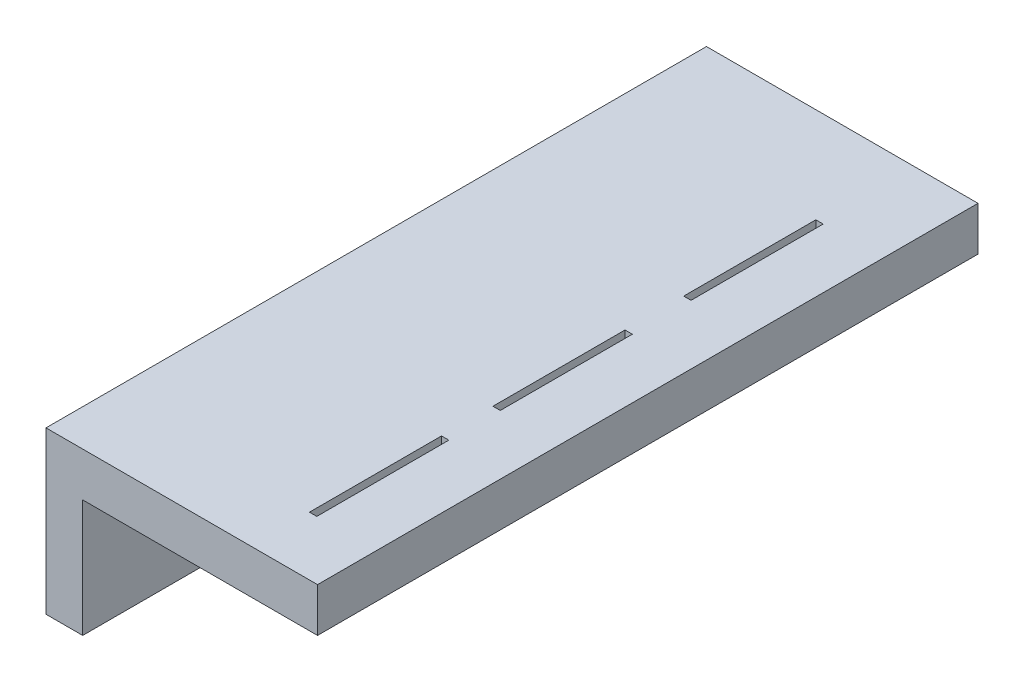
SolidWorks part; units mm, degrees
ref_plane "前视基准面" through (0, 0, 0) normal (0, 0, 1) x (1, 0, 0)
ref_plane "上视基准面" through (0, 0, 0) normal (0, 1, 0) x (1, 0, 0)
ref_plane "右视基准面" through (0, 0, 0) normal (1, 0, 0) x (0, 0, -1)
sketch "Sketch1" plane through (0, 0, 0) normal (0, 1, 0) x (1, 0, 0)
  line L1 (0, 0) -> (70.4, 0)
  line L2 (0, 0) -> (0, 2)
  line L3 (0, 2) -> (70.4, 2)
  line L4 (70.4, 0) -> (70.4, 2)
  dimension "D1" = 70.4
  dimension "D2" = 2
extrude "Boss-Extrude2" add sketch "Sketch1" along normal blind 10
sketch "Sketch2" plane through (0, 10, 0) normal (0, 1, 0) x (1, 0, 0)
  line L1 (0, 2) -> (2, 2)
  line L2 (0, 2) -> (0, 57)
  line L3 (0, 57) -> (2, 57)
  line L4 (2, 2) -> (2, 57)
  line L5 (70.4, 2) -> (68.4, 2)
  line L6 (70.4, 2) -> (70.4, 57)
  line L7 (70.4, 57) -> (68.4, 57)
  line L8 (68.4, 2) -> (68.4, 57)
  dimension "D1" = 55
  dimension "D2" = 2
  dimension "D3" = 2
extrude "Boss-Extrude3" add sketch "Sketch2" against normal blind 10
sketch "Sketch3" plane through (0, 0, 0) normal (0, 0, 1) x (1, 0, 0)
  line L0 (35.2, 0) -> (35.2, 21.6902) construction
  line L1 (0, 0) -> (70.4, 0) construction
  line L2 (0, 10) -> (70.4, 10) construction
  line L3 (25.7, 10) -> (44.7, 10)
  line L4 (25.7, 10) -> (25.7, 13)
  line L5 (25.7, 13) -> (44.7, 13)
  line L6 (44.7, 10) -> (44.7, 13)
  dimension "D1" = 9.5
  dimension "D2" = 9.5
  dimension "D3" = 3
extrude "Boss-Extrude4" add sketch "Sketch3" against normal blind 2
sketch "Sketch4" plane through (0, 0, 0) normal (0, 0, 1) x (1, 0, 0)
  line L0 (35.2, 0) -> (35.2, 21.4055) construction
  line L1 (0, 0) -> (70.4, 0) construction
  line L3 (27.7, 0) -> (42.7, 0)
  line L4 (27.7, 0) -> (27.7, 10)
  line L5 (27.7, 10) -> (42.7, 10)
  line L6 (42.7, 0) -> (42.7, 10)
  dimension "D1" = 10
  dimension "D2" = 7.5
  dimension "D3" = 7.5
extrude "Cut-Extrude2" cut sketch "Sketch4" against normal blind 2
sketch "Sketch5" plane through (25.7, 0, 0) normal (-1, 0, 0) x (0, 0, 1)
  line L1 (-2, 13) -> (0, 13)
  line L2 (-2, 13) -> (-2, 10)
  line L3 (-2, 10) -> (0, 10)
  line L4 (0, 13) -> (0, 10)
extrude "Boss-Extrude5" add sketch "Sketch5" along normal blind 1
sketch "Sketch6" plane through (44.7, 0, 0) normal (1, 0, 0) x (0, 0, -1)
  line L1 (0, 13) -> (2, 13)
  line L2 (0, 13) -> (0, 10)
  line L3 (0, 10) -> (2, 10)
  line L4 (2, 13) -> (2, 10)
extrude "Boss-Extrude6" add sketch "Sketch6" along normal blind 1
sketch "Sketch7" plane through (0, 0, 0) normal (-1, 0, 0) x (0, 0, 1)
  line L0 (0, 10) -> (0, 0) construction
  line L1 (-57, 0) -> (0, 0)
  line L2 (-57, 0) -> (-57, 2)
  line L3 (-57, 2) -> (0, 2)
  line L4 (0, 0) -> (0, 2)
  dimension "D1" = 2
extrude "Boss-Extrude7" add sketch "Sketch7" along normal blind 6.6
sketch "Sketch8" plane through (70.4, 0, 0) normal (1, 0, 0) x (0, 0, -1)
  line L0 (57, 0) -> (57, 10) construction
  line L1 (0, 0) -> (57, 0)
  line L2 (0, 0) -> (0, 2)
  line L3 (0, 2) -> (57, 2)
  line L4 (57, 0) -> (57, 2)
  dimension "D1" = 2
extrude "Boss-Extrude8" add sketch "Sketch8" along normal blind 6.6
sketch "Sketch10" plane through (0, 0, -57) normal (0, 0, -1) x (-1, 0, 0)
  line L0 (-2, 10) -> (-2, 0)
  line L1 (-2, 0) -> (6.6, 0)
  line L2 (6.6, 0) -> (6.6, 2)
  line L3 (6.6, 2) -> (0, 2)
  line L4 (0, 2) -> (0, 10)
  line L5 (0, 10) -> (-2, 10)
  line L6 (-77, 0) -> (-68.4, 0)
  line L7 (-68.4, 0) -> (-68.4, 10)
  line L8 (-68.4, 10) -> (-70.4, 10)
  line L9 (-70.4, 10) -> (-70.4, 2)
  line L10 (-70.4, 2) -> (-77, 2)
  line L11 (-77, 2) -> (-77, 0)
extrude "Boss-Extrude9" add sketch "Sketch10" along normal blind 5
sketch "Sketch12" plane through (0, 10, 0) normal (0, 1, 0) x (1, 0, 0)
  line L0 (0, 0) -> (0, 62) construction
  line L1 (0, 57) -> (2, 57)
  line L2 (0, 57) -> (0, 17)
  line L3 (0, 17) -> (2, 17)
  line L4 (2, 57) -> (2, 17)
  line L5 (2, 2) -> (2, 62) construction
  line L6 (0, 62) -> (2, 62) construction
  line L7 (68.4, 62) -> (68.4, 2) construction
  line L8 (68.4, 57) -> (70.4, 57)
  line L9 (68.4, 57) -> (68.4, 27)
  line L10 (68.4, 27) -> (70.4, 27)
  line L11 (70.4, 57) -> (70.4, 27)
  line L12 (70.4, 62) -> (70.4, 0) construction
  line L13 (68.4, 62) -> (70.4, 62) construction
  line L15 (2, 62) -> (0, 62)
  line L16 (2, 62) -> (2, 57)
  line L17 (2, 57) -> (0, 57)
  line L18 (0, 62) -> (0, 57)
  line L19 (70.4, 62) -> (68.4, 62)
  line L20 (70.4, 62) -> (70.4, 57)
  line L21 (70.4, 57) -> (68.4, 57)
  line L22 (68.4, 62) -> (68.4, 57)
  line M4 (2, 2) -> (2, 62)
  line M5 (2, 62) -> (0, 62)
  line M6 (0, 62) -> (0, 0)
  dimension "D1" = 5
  dimension "D2" = 40
  dimension "D3" = 5
  dimension "D4" = 30
extrude "Boss-Extrude10" add sketch "Sketch12" along normal blind 20 contours L1 M6 M4 M5 | L3 L1 M6 M4 | L11 L8 L9 L10 | L19 L22 L8 L20
sketch "Sketch13" plane through (0, 30, 0) normal (0, 1, 0) x (1, 0, 0)
  line L0 (35.2, 2) -> (35.2, 63.9637) construction
  line L1 (45.7, 2) -> (24.7, 2) construction
  line L2 (0, 17) -> (35.2, 17)
  line L3 (35.2, 17) -> (35.2, 27)
  line L4 (35.2, 27) -> (70.4, 27)
  line L5 (70.4, 27) -> (70.4, 62)
  line L6 (70.4, 62) -> (0, 62)
  line L7 (0, 62) -> (0, 17)
extrude "Boss-Extrude11" add sketch "Sketch13" along normal blind 3
sketch "Sketch14" plane through (0, 33, 0) normal (0, 1, 0) x (1, 0, 0)
  line L0 (35.2, 62) -> (35.2, 11.7147) construction
  line L1 (70.4, 62) -> (0, 62) construction
  line L2 (10.2, 62) -> (10.2, 11.7147) construction
  line L3 (60.2, 62) -> (60.2, 11.7147) construction
  line L4 (10.2, 57) -> (60.2, 57) construction
  line L5 (11.7, 57) -> (11.7, 17) construction
  line L6 (0, 17) -> (35.2, 17) construction
  line L7 (58.2, 57) -> (58.2, 27) construction
  line L8 (35.2, 27) -> (70.4, 27) construction
  line L10 (11.45, 55.5) -> (11.95, 55.5)
  line L11 (11.45, 55.5) -> (11.45, 46.5)
  line L12 (11.45, 46.5) -> (11.95, 46.5)
  line L13 (11.95, 55.5) -> (11.95, 46.5)
  line L14 (11.45, 42.5) -> (11.95, 42.5)
  line L15 (11.45, 42.5) -> (11.45, 33.5)
  line L16 (11.45, 33.5) -> (11.95, 33.5)
  line L17 (11.95, 42.5) -> (11.95, 33.5)
  line L18 (11.45, 30) -> (11.95, 30)
  line L19 (11.45, 30) -> (11.45, 21)
  line L20 (11.45, 21) -> (11.95, 21)
  line L21 (11.95, 30) -> (11.95, 21)
  line L22 (57.95, 55.5) -> (58.45, 55.5)
  line L23 (57.95, 55.5) -> (57.95, 46.5)
  line L24 (57.95, 46.5) -> (58.45, 46.5)
  line L25 (58.45, 55.5) -> (58.45, 46.5)
  line L26 (57.95, 42.5) -> (58.45, 42.5)
  line L27 (57.95, 42.5) -> (57.95, 33.5)
  line L28 (57.95, 33.5) -> (58.45, 33.5)
  line L29 (58.45, 42.5) -> (58.45, 33.5)
  dimension "D1" = 25
  dimension "D2" = 25
  dimension "D3" = 5
  dimension "D4" = 1.5
  dimension "D5" = 2
  dimension "D6" = 0.5
  dimension "D7" = 0.25
  dimension "D8" = 1.5
  dimension "D9" = 9
  dimension "D10" = 4
  dimension "D11" = 9
  dimension "D12" = 9
  dimension "D13" = 3.5
  dimension "D14" = 1.5
  dimension "D15" = 0.25
  dimension "D16" = 0.25
  dimension "D17" = 9
  dimension "D18" = 4
extrude "Cut-Extrude3" cut sketch "Sketch14" against normal blind 3
sketch "Sketch15" plane through (0, 33, 0) normal (0, 1, 0) x (1, 0, 0)
  line L0 (70.4, 62) -> (0, 62) construction
  line L1 (16, 62) -> (54.4, 62)
  line L2 (16, 62) -> (16, 17)
  line L3 (16, 17) -> (54.4, 17)
  line L4 (54.4, 62) -> (54.4, 17)
  line L5 (0, 62) -> (0, 17) construction
  line L6 (70.4, 62) -> (70.4, 0) construction
  dimension "D1" = 16
  dimension "D2" = 16
extrude "Cut-Extrude4" cut sketch "Sketch15" against normal blind 3
sketch "Sketch16" plane through (0, 0, 0) normal (0, 0, 1) x (1, 0, 0)
  line L0 (-6.6, 0) -> (27.7, 0)
  line L1 (27.7, 0) -> (27.7, 10)
  line L2 (27.7, 10) -> (42.7, 10)
  line L3 (42.7, 10) -> (42.7, 0)
  line L4 (42.7, 0) -> (77, 0)
  line L5 (77, 0) -> (77, 2)
  line L6 (77, 2) -> (70.4, 2)
  line L7 (70.4, 2) -> (70.4, 10)
  line L8 (70.4, 10) -> (45.7, 10)
  line L9 (45.7, 10) -> (45.7, 13)
  line L10 (45.7, 13) -> (24.7, 13)
  line L11 (24.7, 13) -> (24.7, 10)
  line L12 (24.7, 10) -> (0, 10)
  line L13 (0, 10) -> (0, 2)
  line L14 (0, 2) -> (-6.6, 2)
  line L15 (-6.6, 2) -> (-6.6, 0)
extrude "Boss-Extrude12" add sketch "Sketch16" along normal blind 0.5
sketch "Sketch17" plane through (0, 2, 0) normal (0, 1, 0) x (1, 0, 0)
  line L0 (-3.3, -0.5) -> (-3.3, 64.6995) construction
  line L1 (0, -0.5) -> (-6.6, -0.5) construction
  line L2 (73.7, -0.5) -> (73.7, 65.8086) construction
  line L3 (77, -0.5) -> (70.4, -0.5) construction
  line L4 (-6.6, 62) -> (0, 62) construction
  line L5 (70.4, 62) -> (77, 62) construction
  line L6 (0, 17) -> (16, 17) construction
  line L7 (-4.8, 17) -> (-1.8, 17)
  line L8 (-4.8, 17) -> (-4.8, 12)
  line L9 (-4.8, 12) -> (-1.8, 12)
  line L10 (-1.8, 17) -> (-1.8, 12)
  line L12 (72.2, 17) -> (75.2, 17)
  line L13 (72.2, 17) -> (72.2, 12)
  line L14 (72.2, 12) -> (75.2, 12)
  line L15 (75.2, 17) -> (75.2, 12)
  circle A0 centre (-3.3, 55) radius 1.8
  circle A1 centre (73.7, 55) radius 1.8
  circle A2 centre (-3.3, 6.5) radius 1.8
  circle A3 centre (73.7, 6.5) radius 1.8
  circle A4 centre (-3.3, 30.75) radius 1.8
  circle A5 centre (73.7, 30.75) radius 1.8
  dimension "D1" = 3.6
  dimension "D2" = 3.6
  dimension "D3" = 3.6
  dimension "D4" = 3.6
  dimension "D9" = 3.6
  dimension "D10" = 3.6
  dimension "D5" = 7
  dimension "D6" = 7
  dimension "D7" = 7
  dimension "D8" = 7
  dimension "D11" = 1.5
  dimension "D12" = 1.5
  dimension "D13" = 5
  dimension "D14" = 0
  dimension "D15" = 1.5
  dimension "D16" = 1.5
extrude "Cut-Extrude6" cut sketch "Sketch17" against normal blind 3
sketch "Sketch19" plane through (70.4, 0, 0) normal (1, 0, 0) x (0, 0, -1)
  line L1 (62, 33) -> (-32.558, 33)
  line L2 (62, 33) -> (62, -18.225)
  line L3 (62, -18.225) -> (-32.558, -18.225)
  line L4 (-32.558, 33) -> (-32.558, -18.225)
extrude "Cut-Extrude8" cut sketch "Sketch19" against normal blind 49 and the other way blind 32
sketch "Sketch20" plane through (2, 0, 0) normal (1, 0, 0) x (0, 0, -1)
  line L1 (62, 30) -> (-29.9454, 30)
  line L2 (62, 30) -> (62, -10.4247)
  line L3 (62, -10.4247) -> (-29.9454, -10.4247)
  line L4 (-29.9454, 30) -> (-29.9454, -10.4247)
extrude "Cut-Extrude9" cut sketch "Sketch20" against normal blind 18 and the other way blind 93
sketch "Sketch21" plane through (0, 0, 0) normal (-1, 0, 0) x (0, 0, 1)
  line L1 (-17, 33) -> (-62, 33)
  line L2 (-17, 33) -> (-17, 30)
  line L3 (-17, 30) -> (-62, 30)
  line L4 (-62, 33) -> (-62, 30)
extrude "Boss-Extrude14" add sketch "Sketch21" along normal blind 2.5
sketch "Sketch22" plane through (0, 30, 0) normal (0, -1, 0) x (1, 0, 0)
  line L0 (16, -62) -> (-2.5, -62) construction
  line L1 (-2.5, -17) -> (0, -17)
  line L2 (-2.5, -17) -> (-2.5, -62)
  line L3 (-2.5, -62) -> (0, -62)
  line L4 (0, -17) -> (0, -62)
  dimension "D1" = 2.5
extrude "Boss-Extrude15" add sketch "Sketch22" along normal blind 8
sketch "Sketch23" plane through (0, 0, 0) normal (1, 0, 0) x (0, 0, -1)
  line L0 (17, 26) -> (66.1526, 26) construction
  line L1 (17, 22) -> (17, 30) construction
  line L2 (62, 22) -> (62, 30) construction
  circle A0 centre (27, 26) radius 1.8
  circle A1 centre (52, 26) radius 1.8
  dimension "D1" = 3.6
  dimension "D2" = 3.6
  dimension "D3" = 10
  dimension "D4" = 10
extrude "Cut-Extrude10" cut sketch "Sketch23" against normal blind 10
